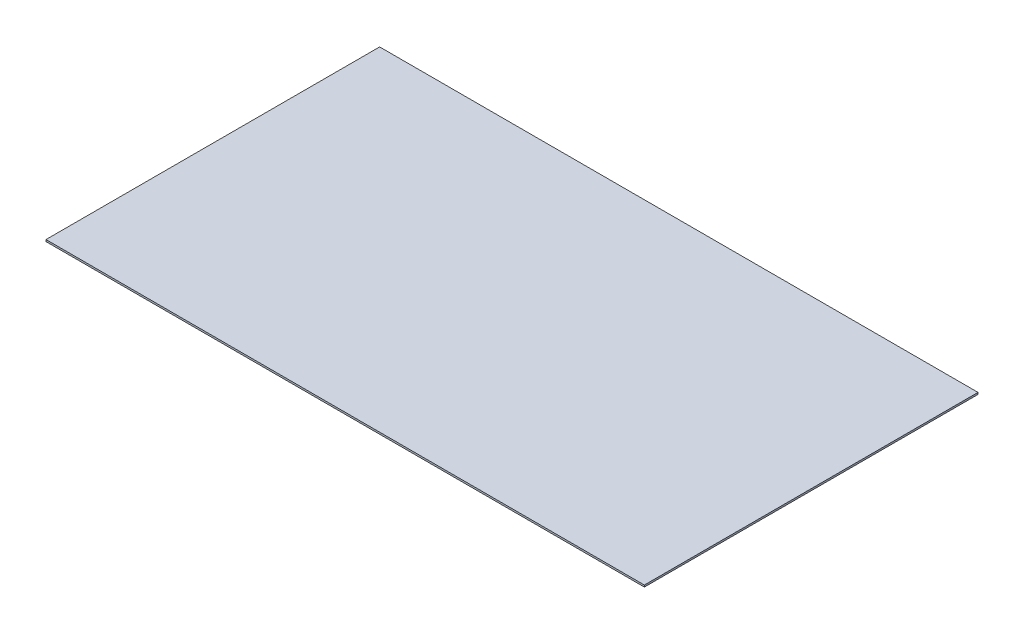
SolidWorks part; units mm, degrees
ref_plane "Front Plane" through (0, 0, 0) normal (0, 0, 1) x (1, 0, 0)
ref_plane "Top Plane" through (0, 0, 0) normal (0, 1, 0) x (1, 0, 0)
ref_plane "Right Plane" through (0, 0, 0) normal (1, 0, 0) x (0, 0, -1)
sketch "Sketch1" plane through (0, 0, 0) normal (0, 1, 0) x (1, 0, 0)
  line L1 (0, 0) -> (165, 0)
  line L2 (0, 0) -> (0, 92)
  line L3 (0, 92) -> (165, 92)
  line L4 (165, 0) -> (165, 92)
  dimension "D1" = 165
  dimension "D2" = 92
extrude "Boss-Extrude1" add sketch "Sketch1" along normal blind 0.5
